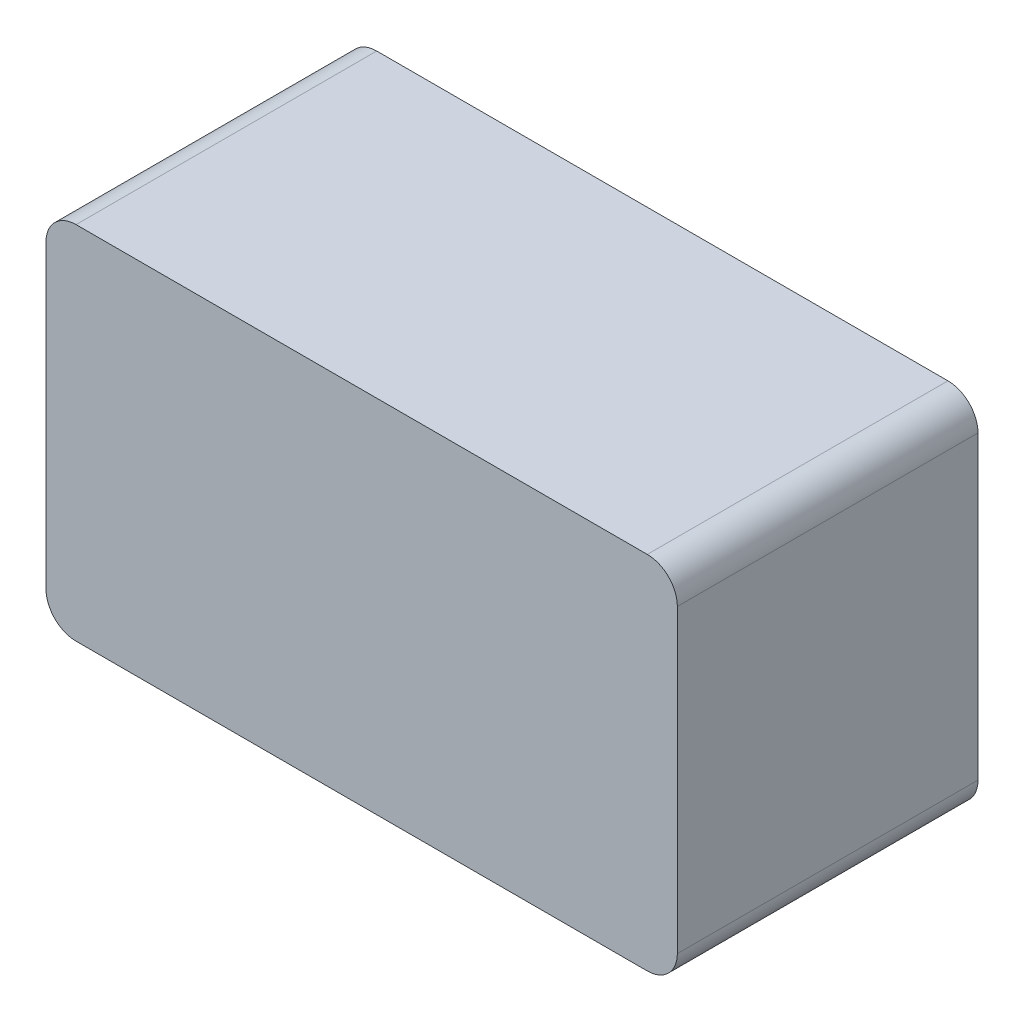
SolidWorks part; units mm, degrees
ref_plane "Front Plane" through (0, 0, 0) normal (0, 0, 1) x (1, 0, 0)
ref_plane "Top Plane" through (0, 0, 0) normal (0, 1, 0) x (1, 0, 0)
ref_plane "Right Plane" through (0, 0, 0) normal (1, 0, 0) x (0, 0, -1)
sketch "Sketch2" plane through (0, 0, 0) normal (0, 0, 1) x (1, 0, 0)
  line L1 (-9.5, 6) -> (9.5, 6)
  line L2 (-10.5, 5) -> (-10.5, -5)
  line L3 (-9.5, -6) -> (9.5, -6)
  line L4 (10.5, 5) -> (10.5, -5)
  line L5 (-10.5, 6) -> (10.5, -6) construction
  line L6 (-10.5, -6) -> (10.5, 6) construction
  arc A0 (-10.5, -5) -> (-9.5, -6) centre (-9.5, -5) ccw
  arc A1 (9.5, -6) -> (10.5, -5) centre (9.5, -5) ccw
  arc A2 (10.5, 5) -> (9.5, 6) centre (9.5, 5) ccw
  arc A3 (-9.5, 6) -> (-10.5, 5) centre (-9.5, 5) ccw
  point P0 (0, 0)
  dimension "D3" = 1
  dimension "D1" = 21
  dimension "D2" = 12
extrude "Boss-Extrude2" add sketch "Sketch2" along normal blind 10
sketch "Sketch4" plane through (0, 0, 0) normal (0, 0, -1) x (-1, 0, 0)
  line L1 (-9.7598, 5.3529) -> (9.7402, 5.3529)
  line L2 (-9.8598, 5.2529) -> (-9.8598, -5.2966)
  line L3 (-9.7598, -5.3966) -> (9.7402, -5.3966)
  line L4 (9.8402, 5.2529) -> (9.8402, -5.2966)
  arc A0 (9.8402, -5.2966) -> (9.7402, -5.3966) centre (9.7402, -5.2966) cw
  arc A1 (9.8402, 5.2529) -> (9.7402, 5.3529) centre (9.7402, 5.2529) ccw
  arc A2 (-9.7598, -5.3966) -> (-9.8598, -5.2966) centre (-9.7598, -5.2966) cw
  arc A3 (-9.7598, 5.3529) -> (-9.8598, 5.2529) centre (-9.7598, 5.2529) ccw
  point P8 (9.8402, 5.3529)
  point P11 (-9.8598, -5.3966)
  point P14 (-9.8598, 5.3529)
  dimension "D3" = 0.1
  dimension "D1" = 19.7
  dimension "D2" = 10.7495
extrude "Cut-Extrude3" cut sketch "Sketch4" against normal blind 1.6
ref_plane "Plane1" through (-9.8, 0, 0) normal (-1, 0, 0) x (0, 0, 1)
sketch "Sketch5" plane through (-9.8, 0, 0) normal (-1, 0, 0) x (0, 0, 1)
  line L1 (9.7997, 4.886) -> (1.6348, 4.886)
  line L2 (9.7997, 4.886) -> (9.7997, -4.8752)
  line L3 (9.7997, -4.8752) -> (1.6348, -4.8752)
  line L4 (1.6348, 4.886) -> (1.6348, -4.8752)
extrude "Cut-Extrude4" cut sketch "Sketch5" against normal blind 19.6
sketch "Sketch6" plane through (0, -6, 0) normal (0, -1, 0) x (1, 0, 0)
  circle A0 centre (0, 5) radius 1
  dimension "D1" = 2
extrude "Cut-Extrude5" cut sketch "Sketch6" against normal blind 5
